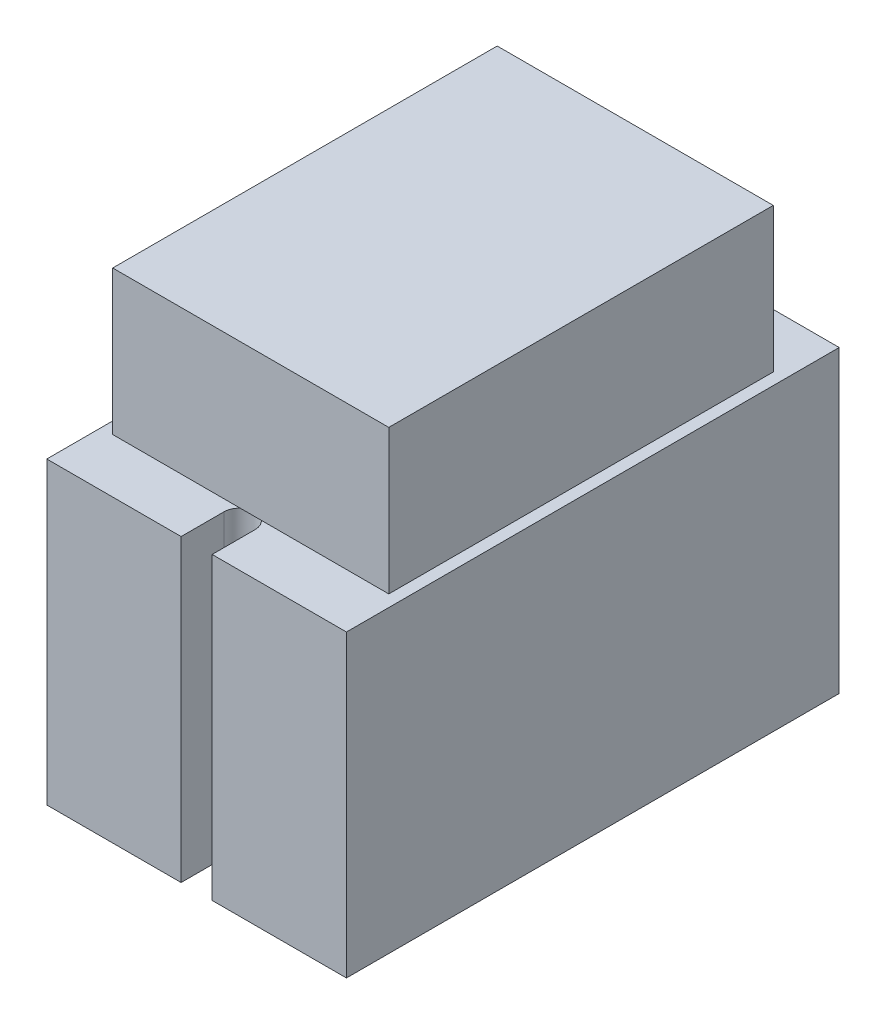
SolidWorks part; units mm, degrees
ref_plane "Front Plane" through (0, 0, 0) normal (0, 0, 1) x (1, 0, 0)
ref_plane "Top Plane" through (0, 0, 0) normal (0, 1, 0) x (1, 0, 0)
ref_plane "Right Plane" through (0, 0, 0) normal (1, 0, 0) x (0, 0, -1)
sketch "Sketch1" plane through (0, 0, 0) normal (0, 1, 0) x (1, 0, 0)
  line L0 (24.5364, 80.6958) -> (24.5364, 0) construction
  line L1 (0, 0) -> (49.0728, 0)
  line L2 (0, 0) -> (0, 80.6958)
  line L3 (0, 80.6958) -> (49.0728, 80.6958)
  line L4 (49.0728, 0) -> (49.0728, 80.6958)
  line L5 (0, 40.3479) -> (49.0728, 40.3479) construction
  line L6 (21.9964, 73.6854) -> (21.9964, 80.6958)
  line L7 (27.0764, 73.6854) -> (27.0764, 80.6958)
  line L8 (27.0764, 7.0104) -> (27.0764, 0)
  line L9 (21.9964, 7.0104) -> (21.9964, 0)
  circle A0 centre (24.5364, 73.6854) radius 2.54
  circle A1 centre (24.5364, 7.0104) radius 2.54
  dimension "D3" = 5.08
  dimension "D1" = 49.0728
  dimension "D2" = 80.6958
  dimension "D4" = 33.3375
extrude "Boss-Extrude1" add sketch "Sketch1" along normal blind 49.0728 contours L9 A1 L8 L1 L4 L3 L7 A0 L6 L2
sketch "Sketch2" plane through (0, 49.0728, 0) normal (0, 1, 0) x (1, 0, 0)
  line L0 (0, 0) -> (49.0728, 80.6958) construction
  line L2 (1.9304, 71.8312) -> (47.1424, 71.8312)
  line L3 (1.9304, 71.8312) -> (1.9304, 8.8646)
  line L4 (1.9304, 8.8646) -> (47.1424, 8.8646)
  line L5 (47.1424, 71.8312) -> (47.1424, 8.8646)
  line L6 (1.9304, 71.8312) -> (47.1424, 8.8646) construction
  line L7 (1.9304, 8.8646) -> (47.1424, 71.8312) construction
  point P4 (24.5364, 40.3479)
  dimension "D1" = 45.212
  dimension "D2" = 62.9666
extrude "Boss-Extrude2" add sketch "Sketch2" along normal blind 23.622
